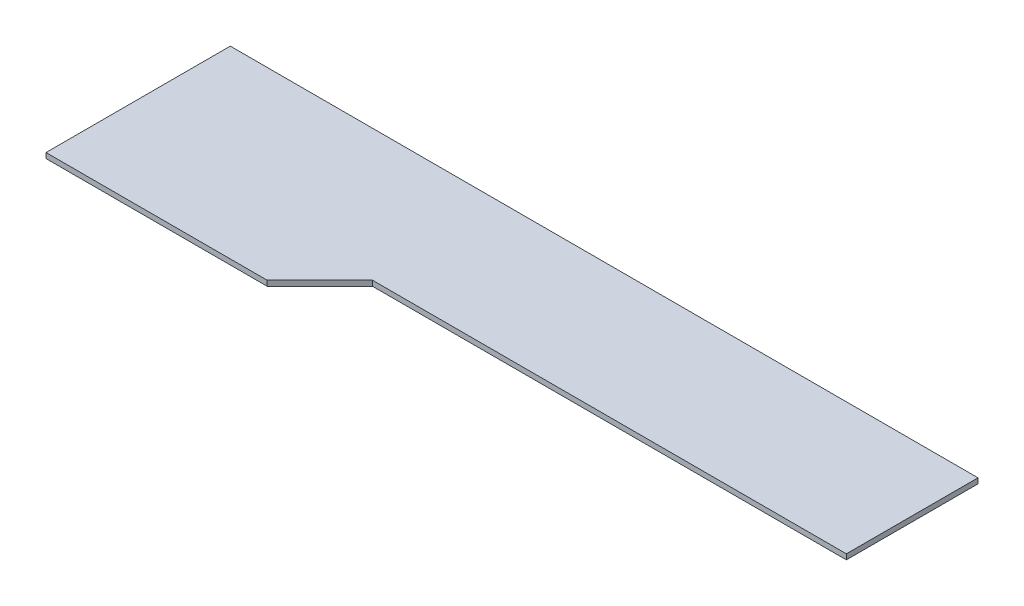
SolidWorks part; units mm, degrees
material "Бук"
ref_plane "Спереди" through (0, 0, 0) normal (0, 0, 1) x (1, 0, 0)
ref_plane "Сверху" through (0, 0, 0) normal (0, 1, 0) x (1, 0, 0)
ref_plane "Справа" through (0, 0, 0) normal (1, 0, 0) x (0, 0, -1)
sketch "Эскиз1" plane through (0, 0, 0) normal (0, 1, 0) x (1, 0, 0)
  line L0 (420, -100) -> (520, 0)
  line L1 (520, 0) -> (1420, 0)
  line L2 (0, 0) -> (0, 250)
  line L3 (0, 250) -> (1420, 250)
  line L4 (1420, 0) -> (1420, 250)
  line L6 (0, 0) -> (0, -100)
  line L7 (0, -100) -> (420, -100)
  dimension "D1" = 1420
  dimension "D2" = 250
  dimension "D3" = 100
  dimension "D4" = 420
extrude "Бобышка-Вытянуть1" add sketch "Эскиз1" along normal blind 10
